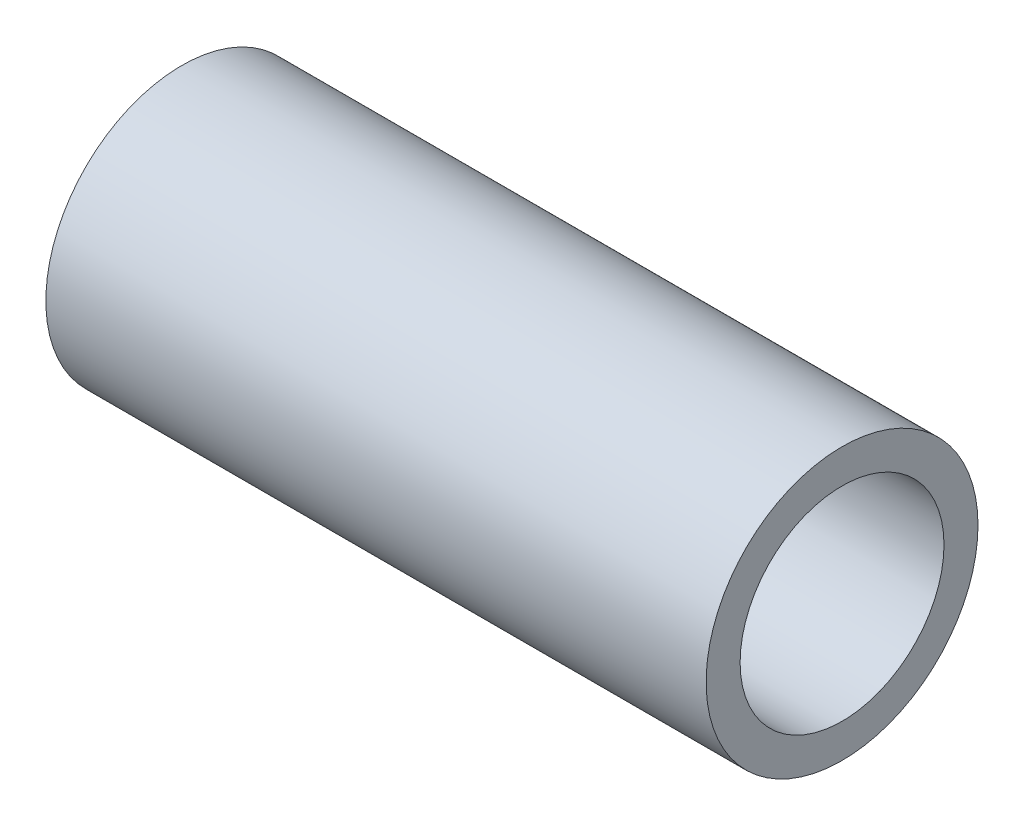
SolidWorks part; units mm, degrees
material "AISI 1020"
ref_plane "Front Plane" through (0, 0, 0) normal (0, 0, 1) x (1, 0, 0)
ref_plane "Top Plane" through (0, 0, 0) normal (0, 1, 0) x (1, 0, 0)
ref_plane "Right Plane" through (0, 0, 0) normal (1, 0, 0) x (0, 0, -1)
sketch "Sketch1" plane through (0, 0, 0) normal (1, 0, 0) x (0, 0, -1)
  circle A0 centre (0, 0) radius 7
  circle A1 centre (0, 0) radius 5.25
  dimension "D1" = 14
  dimension "D2" = 1.75
extrude "Boss-Extrude1" add sketch "Sketch1" along normal blind 34
